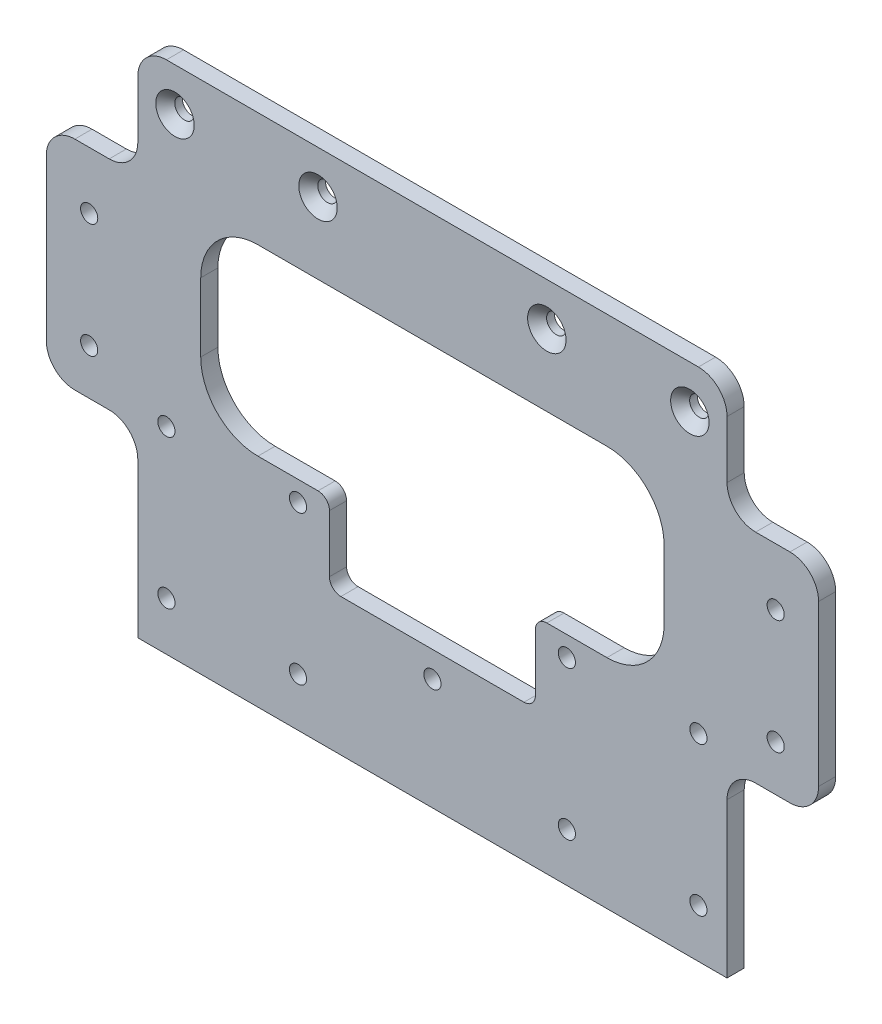
SolidWorks part; units mm, degrees
material "Thornel Mat VMA"
ref_plane "前视基准面" through (0, 0, 0) normal (0, 0, 1) x (1, 0, 0)
ref_plane "上视基准面" through (0, 0, 0) normal (0, 1, 0) x (1, 0, 0)
ref_plane "右视基准面" through (0, 0, 0) normal (1, 0, 0) x (0, 0, -1)
sketch "草图1" plane through (0, 0, 0) normal (0, 0, 1) x (1, 0, 0)
  line L0 (0, 0) -> (0, 110.3127) construction
  line L1 (51.5, 90) -> (-51.5, 90)
  line L2 (-51.5, 90) -> (-51.5, 70)
  line L3 (51.5, 90) -> (51.5, 70)
  line L4 (-51.5, 70) -> (-67.5, 70)
  line L5 (51.5, 70) -> (67.5, 70)
  line L6 (-67.5, 70) -> (-67.5, 32)
  line L7 (67.5, 70) -> (67.5, 32)
  line L8 (-67.5, 32) -> (-51.5, 32)
  line L9 (67.5, 32) -> (51.5, 32)
  line L10 (-51.5, 32) -> (-51.5, 0)
  line L11 (51.5, 32) -> (51.5, 0)
  line L12 (-51.5, 0) -> (51.5, 0)
  line L13 (0, 0) -> (0, -79.7117) construction
  point P6 (0, 90)
  point P17 (0, 0)
  dimension "D1" = 135
  dimension "D2" = 16
  dimension "D3" = 20
  dimension "D4" = 90
  dimension "D5" = 58
extrude "凸台-拉伸1" add sketch "草图1" along normal blind 3
fillet "圆角1" radius 5 10 edges at (-51.5, 90, 1.5) (-51.5, 70, 1.5) (-67.5, 70, 1.5) (-67.5, 32, 1.5) (-51.5, 32, 1.5) (51.5, 32, 1.5) (67.5, 32, 1.5) (67.5, 70, 1.5) (51.5, 90, 1.5) (51.5, 70, 1.5)
sketch "草图2" plane through (0, 0, 3) normal (0, 0, 1) x (1, 0, 0)
  line L0 (0, 90) -> (0, 0) construction
  line L1 (46.5, 90) -> (-46.5, 90) construction
  line L2 (-67.5, 65) -> (-67.5, 37) construction
  circle A1 centre (-45, 82.5) radius 1.5
  circle A2 centre (45, 82.5) radius 1.5
  circle A3 centre (-20, 82.5) radius 1.5
  circle A4 centre (20, 82.5) radius 1.5
  circle A5 centre (-60, 60) radius 1.5
  circle A6 centre (60, 60) radius 1.5
  circle A7 centre (-60, 40) radius 1.5
  circle A8 centre (60, 40) radius 1.5
  dimension "D1" = 3
  dimension "D2" = 20
  dimension "D3" = 25
  dimension "D4" = 7.5
  dimension "D5" = 20
  dimension "D6" = 30
  dimension "D7" = 7.5
extrude "切除-拉伸1" cut sketch "草图2" against normal through all
sketch "草图4" plane through (0, 0, 3) normal (0, 0, 1) x (1, 0, 0)
  line L1 (-46.5, 34.5) -> (-23.5, 34.5) construction
  line L2 (-46.5, 34.5) -> (-46.5, 8.5) construction
  line L3 (-46.5, 8.5) -> (-23.5, 8.5) construction
  line L4 (-23.5, 34.5) -> (-23.5, 8.5) construction
  line L5 (-46.5, 34.5) -> (-23.5, 8.5) construction
  line L6 (-46.5, 8.5) -> (-23.5, 34.5) construction
  line L7 (0, 90) -> (0, 0) construction
  line L8 (46.5, 90) -> (-46.5, 90) construction
  line L9 (46.5, 8.5) -> (23.5, 34.5) construction
  line L10 (46.5, 34.5) -> (23.5, 8.5) construction
  line L11 (23.5, 34.5) -> (23.5, 8.5) construction
  line L12 (46.5, 8.5) -> (23.5, 8.5) construction
  line L13 (46.5, 34.5) -> (46.5, 8.5) construction
  line L14 (46.5, 34.5) -> (23.5, 34.5) construction
  circle A0 centre (-46.5, 34.5) radius 1.5
  circle A1 centre (-23.5, 34.5) radius 1.5
  circle A2 centre (-23.5, 8.5) radius 1.5
  circle A3 centre (-46.5, 8.5) radius 1.5
  circle A4 centre (46.5, 8.5) radius 1.5
  circle A5 centre (23.5, 8.5) radius 1.5
  circle A6 centre (23.5, 34.5) radius 1.5
  circle A7 centre (46.5, 34.5) radius 1.5
  point P0 (-35, 21.5)
  point P22 (35, 21.5)
  dimension "D3" = 3
  dimension "D1" = 23
  dimension "D2" = 26
  dimension "D4" = 35
  dimension "D5" = 81.5
extrude "切除-拉伸2" cut sketch "草图4" against normal through all
sketch "草图6" plane through (0, 0, 3) normal (0, 0, 1) x (1, 0, 0)
  line L0 (0, 90) -> (0, 0) construction
  line L1 (46.5, 90) -> (-46.5, 90) construction
  circle A0 centre (0, 19.5) radius 1.5
  dimension "D1" = 70.5
  dimension "D2" = 3
extrude "切除-拉伸3" cut sketch "草图6" against normal through all
sketch "草图7" plane through (0, 0, 3) normal (0, 0, 1) x (1, 0, 0)
  line L0 (0, 90) -> (0, 0) construction
  line L1 (46.5, 90) -> (-46.5, 90) construction
  line L2 (62.5, 70) -> (56.5, 70) construction
  line L3 (-40.5, 70) -> (40.5, 70)
  line L4 (-40.5, 70) -> (-40.5, 38)
  line L5 (-40.5, 38) -> (40.5, 38)
  line L6 (40.5, 70) -> (40.5, 38)
  line L7 (-40.5, 70) -> (40.5, 38) construction
  line L8 (-40.5, 38) -> (40.5, 70) construction
  line L9 (51.5, 0) -> (51.5, 27) construction
  point P5 (0, 54)
  dimension "D1" = 11
  dimension "D3" = 32
extrude "切除-拉伸4" cut sketch "草图7" against normal through all
fillet "圆角2" radius 10 4 edges at (-40.5, 38, 1.5) (40.5, 38, 1.5) (40.5, 70, 1.5) (-40.5, 70, 1.5)
sketch "草图8" plane through (0, 0, 3) normal (0, 0, 1) x (1, 0, 0)
  line L0 (-30.5, 38) -> (30.5, 38) construction
  line L1 (-18, 38) -> (18, 38)
  line L2 (-18, 38) -> (-18, 24)
  line L3 (-18, 24) -> (18, 24)
  line L4 (18, 38) -> (18, 24)
  line L5 (0, 24) -> (0, 0) construction
  dimension "D1" = 14
  dimension "D2" = 36
extrude "切除-拉伸5" cut sketch "草图8" against normal through all
fillet "圆角3" radius 2 4 edges at (-18, 38, 1.5) (18, 38, 1.5) (18, 24, 1.5) (-18, 24, 1.5)
hole_wizard "M3 六角凹锥坑螺钉的锥形沉头孔1" positions "3D草图1" profile "草图9" countersink size "M3" standard "ISO" end condition through all
sketch3d "3D草图1"
  line L0 (-45, 82.5, 0) -> (-45, 82.5, 3) construction
  line L1 (-20, 82.5, 0) -> (-20, 82.5, 3) construction
  line L2 (20, 82.5, 0) -> (20, 82.5, 3) construction
  line L3 (45, 82.5, 0) -> (45, 82.5, 3) construction
  point P0 (-45, 82.5, 3)
  point P4 (-20, 82.5, 3)
  point P8 (20, 82.5, 3)
  point P12 (45, 82.5, 3)
sketch "草图9" plane through (-45, 82.5, 3) normal (1, 0, 0) x (0, -1, 0)
  line L0 (0, 0) -> (0, 3)
  line L1 (0, 3) -> (1.7, 3)
  line L2 (1.7, 3) -> (1.7, 1.66)
  line L3 (1.7, 1.66) -> (3.36, 0)
  line L5 (3.36, 0) -> (0, 0)
  line L6 (-1.7, 1.66) -> (-3.36, 0) construction
  line L11 (0, -6.35) -> (0, 107.95) construction
  dimension "通孔孔直径" = 3.4
  dimension "通孔孔深度" = 3
  dimension "近端锥形沉头孔直径" = 6.72
  dimension "近端锥形沉头孔角度" = 90
